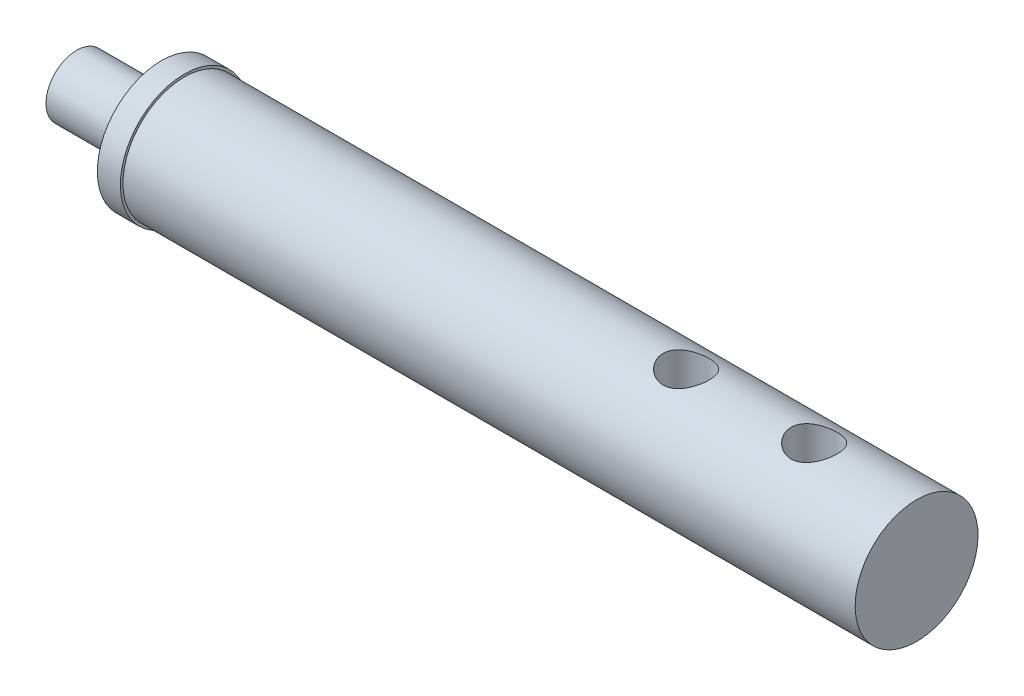
SolidWorks part; units mm, degrees
ref_plane "Front Plane" through (0, 0, 0) normal (0, 0, 1) x (1, 0, 0)
ref_plane "Top Plane" through (0, 0, 0) normal (0, 1, 0) x (1, 0, 0)
ref_plane "Right Plane" through (0, 0, 0) normal (1, 0, 0) x (0, 0, -1)
sketch "Sketch1" plane through (0, 0, 0) normal (0, 0, 1) x (1, 0, 0)
  line L0 (108.6771, 12) -> (-34.3229, 12)
  line L2 (-34.3229, 12.5) -> (-38.8229, 12.5)
  line L3 (-38.8229, 12.5) -> (-38.8229, 6)
  line L4 (-38.8229, 6) -> (-55.3529, 6)
  line L5 (-55.3529, 6) -> (-55.3529, 0)
  line L11 (108.6771, 0) -> (108.6771, 12)
  line L12 (108.6771, 0) -> (-133.6321, 0) construction
  line L14 (-34.3229, 12.5) -> (-34.3229, 12)
  line L15 (-55.3529, 0) -> (108.6771, 0)
  dimension "D3" = 143
  dimension "D4" = 4.5
  dimension "D5" = 16.53
  dimension "D6" = 12
revolve "Revolve1" add sketch "Sketch1" angle 360 about L12
sketch "Sketch2" plane through (0, 0, 0) normal (0, 1, 0) x (1, 0, 0)
  line L1 (108.6771, -12) -> (108.6771, 12) construction
  circle A0 centre (88.6771, 0) radius 4.5
  circle A1 centre (63.6771, 0) radius 4.5
  point P2 (73.1008, 0)
  point P3 (98.3566, 0)
  dimension "D1" = 9
  dimension "D3" = 9
  dimension "D4" = 25
  dimension "D2" = 20
extrude "Cut-Extrude1" cut sketch "Sketch2" against normal through all both and the other way through all
